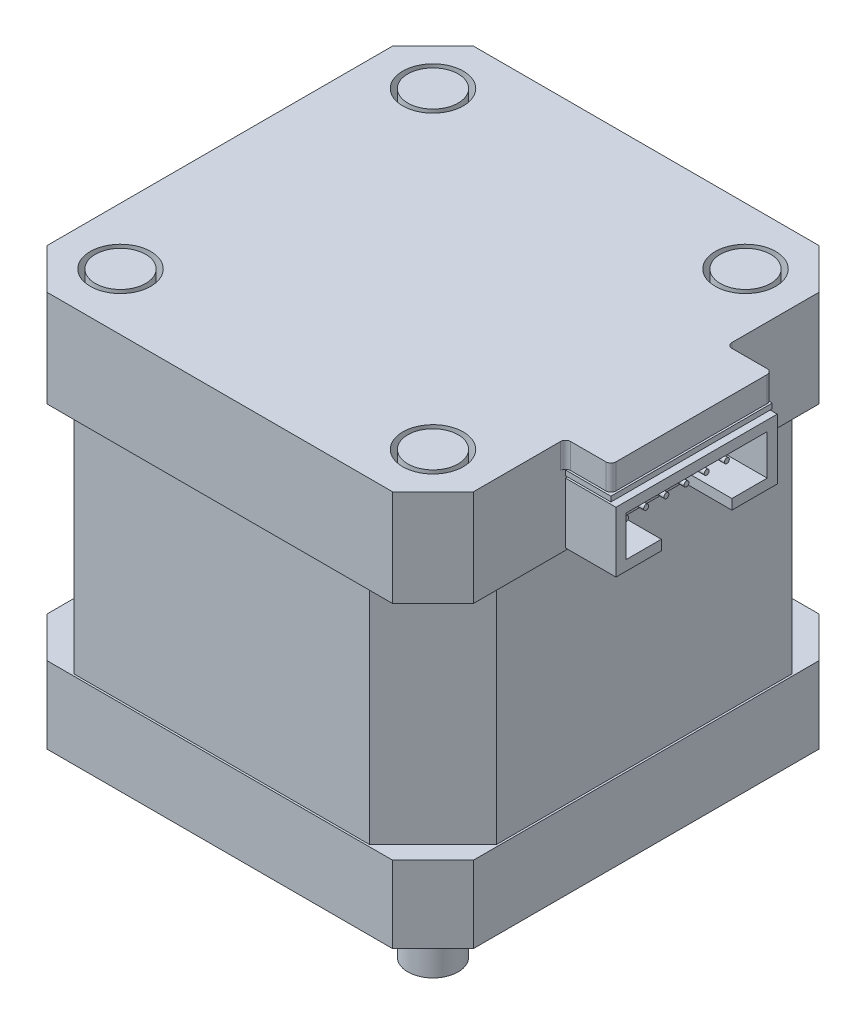
SolidWorks part; units mm, degrees
ref_plane "Front Plane" through (0, 0, 0) normal (0, 0, 1) x (1, 0, 0)
ref_plane "Top Plane" through (0, 0, 0) normal (0, 1, 0) x (1, 0, 0)
ref_plane "Right Plane" through (0, 0, 0) normal (1, 0, 0) x (0, 0, -1)
sketch "Sketch1" plane through (0, 0, 0) normal (0, 1, 0) x (1, 0, 0)
  line L1 (-21.15, -21.15) -> (21.15, -21.15)
  line L2 (-21.15, -21.15) -> (-21.15, 21.15)
  line L3 (-21.15, 21.15) -> (21.15, 21.15)
  line L4 (21.15, -21.15) -> (21.15, 21.15)
  line L5 (-21.15, -21.15) -> (21.15, 21.15) construction
  line L6 (-21.15, 21.15) -> (21.15, -21.15) construction
  point P0 (0, 0)
  dimension "D1" = 42.3
  dimension "D2" = 42.3
extrude "Boss-Extrude1" add sketch "Sketch1" along normal blind 39.25
chamfer "Chamfer1" distance 4 angle 45 8 edges at (-21.15, 19.625, -21.15) (21.15, 19.625, -21.15) (21.15, 19.625, 21.15) (-21.15, 19.625, 21.15) (21.15, 0, 0) (21.15, 39.25, 0) (-21.15, 39.25, 0) (-21.15, 0, 0)
sketch "Sketch2" plane through (19.15, 0, -19.15) normal (0.7071, 0, -0.7071) x (-0.7071, 0, -0.7071)
  line L0 (2.8284, 0) -> (-2.8284, 0) construction
  line L1 (-4.9984, 29.65) -> (5.0016, 29.65)
  line L2 (-4.9984, 29.65) -> (-4.9984, 7.6)
  line L3 (-4.9984, 7.6) -> (5.0016, 7.6)
  line L4 (5.0016, 29.65) -> (5.0016, 7.6)
  line L5 (-2.8284, 39.25) -> (2.8284, 39.25) construction
  line L6 (-2.8284, 0) -> (-2.8284, 39.25) construction
  line L8 (2.8284, 39.25) -> (2.8284, 0) construction
  dimension "D1" = 7.6
  dimension "D2" = 9.6
  dimension "D3" = 2.17
  dimension "D4" = 10
extrude "Cut-Extrude1" cut sketch "Sketch2" against normal blind 1.9
mirror "Mirror1" about plane through (0, 0, 0) normal (0, 0, 1) of "Cut-Extrude1"
mirror "Mirror2" about plane through (0, 0, 0) normal (1, 0, 0) of "Mirror1", "Cut-Extrude1"
sketch "Sketch3" plane through (0, 0, 0) normal (0, -1, 0) x (1, 0, 0)
  circle A0 centre (0, 0) radius 11
  dimension "D1" = 22
extrude "Boss-Extrude2" add sketch "Sketch3" along normal blind 1.9
sketch "Sketch4" plane through (0, 0, 0) normal (0, -1, 0) x (1, 0, 0)
  circle A0 centre (0, 0) radius 11.5
  circle A1 centre (0, 0) radius 11
  dimension "D1" = 0.5
extrude "Cut-Extrude2" cut sketch "Sketch4" against normal blind 2
sketch "Sketch5" plane through (0, -1.9, 0) normal (0, -1, 0) x (1, 0, 0)
  circle A0 centre (0, 0) radius 4.5
  dimension "D1" = 9
extrude "Cut-Extrude3" cut sketch "Sketch5" against normal blind 2
sketch "Sketch6" plane through (0, 0.1, 0) normal (0, -1, 0) x (1, 0, 0)
  circle A0 centre (0, 0) radius 2.5
  dimension "D1" = 5
extrude "Boss-Extrude3" add sketch "Sketch6" along normal blind 20
sketch "Sketch7" plane through (0, -19.9, 0) normal (0, -1, 0) x (1, 0, 0)
  line L0 (-2.5, 0) -> (0, -2.5)
  line L1 (0, 0) -> (0, -2.5) construction
  line L2 (0, 0) -> (-2.5, 0) construction
  arc A0 (-2.5, 0) -> (0, -2.5) centre (0, 0) ccw
  circle A1 centre (0, 0) radius 2.5 construction
  circle A2 centre (0, 0) radius 2.5 construction
extrude "Cut-Extrude4" cut sketch "Sketch7" against normal blind 15
sketch "Sketch8" plane through (0, 0, 0) normal (0, -1, 0) x (1, 0, 0)
  line L1 (-15.5, -15.5) -> (15.5, -15.5) construction
  line L2 (-15.5, -15.5) -> (-15.5, 15.5) construction
  line L3 (-15.5, 15.5) -> (15.5, 15.5) construction
  line L4 (15.5, -15.5) -> (15.5, 15.5) construction
  line L5 (-15.5, -15.5) -> (15.5, 15.5) construction
  line L6 (-15.5, 15.5) -> (15.5, -15.5) construction
  circle A0 centre (-15.5, 15.5) radius 1.5
  circle A1 centre (15.5, 15.5) radius 1.5
  circle A2 centre (15.5, -15.5) radius 1.5
  circle A3 centre (-15.5, -15.5) radius 1.5
  point P0 (0, 0)
  point P16 (0, 0)
  dimension "D4" = 3
  dimension "D1" = 31
  dimension "D2" = 31
  dimension "D3" = 4
extrude "Cut-Extrude5" cut sketch "Sketch8" against normal blind 4
sketch "Sketch10" plane through (-21.15, 0, 0) normal (-1, 0, 0) x (0, 0, 1)
  line L0 (-17.15, 7.6) -> (-14.463, 7.6) construction
  line L1 (-15.463, 7.6) -> (15.463, 7.6)
  line L2 (-15.463, 7.6) -> (-15.463, 29.65)
  line L3 (-15.463, 29.65) -> (15.463, 29.65)
  line L4 (15.463, 7.6) -> (15.463, 29.65)
  line L5 (21.15, 29.65) -> (14.463, 29.65) construction
  line L6 (-14.463, 7.6) -> (-14.463, 29.65) construction
  line L7 (14.463, 29.65) -> (14.463, 7.6) construction
  dimension "D1" = 1
  dimension "D2" = 1
extrude "Cut-Extrude6" cut sketch "Sketch10" against normal blind 0.2
pattern_circular "CirPattern1" count 4 every 90 about axis through (0, 0, 0) along (0, 1, 0) of "Cut-Extrude6"
sketch "Sketch11" plane through (21.15, 0, 0) normal (1, 0, 0) x (0, 0, -1)
  line L0 (-17.15, 39.25) -> (17.15, 39.25) construction
  line L1 (-8, 39.25) -> (8, 39.25)
  line L2 (-8, 39.25) -> (-8, 36.75)
  line L3 (-8, 36.75) -> (8, 36.75)
  line L4 (8, 39.25) -> (8, 36.75)
  line L6 (0, 0) -> (0, 39.25) construction
  point P9 (0, 39.25)
  dimension "D1" = 16
  dimension "D2" = 2.5
extrude "Boss-Extrude4" add sketch "Sketch11" along normal blind 4.5
fillet "Fillet1" radius 0.5 4 edges at (21.15, 38, -8) (25.65, 38, -8) (21.15, 38, 8) (25.65, 38, 8)
sketch "Sketch12" plane through (21.15, 0, 0) normal (1, 0, 0) x (0, 0, -1)
  line L0 (-7.5, 36.75) -> (7.5, 36.75) construction
  line L1 (-8, 36.55) -> (8, 36.55)
  line L2 (-8, 36.55) -> (-8, 36.05)
  line L3 (-8, 36.05) -> (8, 36.05)
  line L4 (8, 36.55) -> (8, 36.05)
  line L5 (-8, 39.25) -> (-8, 36.75) construction
  line L7 (8, 36.75) -> (8, 39.25) construction
  dimension "D1" = 0.2
  dimension "D2" = 0.5
extrude "Boss-Extrude5" add sketch "Sketch12" along normal blind 4.5
sketch "Sketch13" plane through (21.15, 0, 0) normal (1, 0, 0) x (0, 0, -1)
  line L0 (-3.5, 30.85) -> (-3.5, 29.85)
  line L1 (-8, 35.85) -> (8, 35.85)
  line L2 (-8, 35.85) -> (-8, 29.85)
  line L3 (-8, 29.85) -> (-3.5, 29.85)
  line L4 (8, 35.85) -> (8, 29.85)
  line L5 (-7, 34.85) -> (7, 34.85)
  line L6 (-7, 34.85) -> (-7, 30.85)
  line L7 (-7, 30.85) -> (-3.5, 30.85)
  line L8 (7, 34.85) -> (7, 30.85)
  line L9 (3.5, 30.85) -> (3.5, 29.85)
  line L10 (3.5, 30.85) -> (7, 30.85)
  line L11 (3.5, 29.85) -> (8, 29.85)
  line L12 (8, 36.05) -> (8, 36.55) construction
  line L13 (-8, 36.55) -> (-8, 36.05) construction
  line L14 (-8, 36.05) -> (8, 36.05) construction
  line L15 (14.663, 29.65) -> (-14.663, 29.65) construction
  dimension "D1" = 0.2
  dimension "D2" = 0.2
  dimension "D3" = 1
  dimension "D4" = 1
  dimension "D5" = 1
  dimension "D6" = 1
  dimension "D7" = 3.5
  dimension "D8" = 3.5
extrude "Boss-Extrude6" add sketch "Sketch13" along normal blind 5
sketch "Sketch14" plane through (21.15, 0, 0) normal (1, 0, 0) x (0, 0, -1)
  line L0 (-7, 32.35) -> (7, 32.35) construction
  line L1 (-7, 30.85) -> (-7, 34.85) construction
  line L2 (7, 34.85) -> (7, 30.85) construction
  line L3 (-3.5, 30.85) -> (-7, 30.85) construction
  circle A0 centre (-5, 32.35) radius 0.25
  circle A1 centre (-3, 32.35) radius 0.25
  circle A2 centre (-1, 32.35) radius 0.25
  circle A3 centre (1, 32.35) radius 0.25
  circle A4 centre (3, 32.35) radius 0.25
  circle A5 centre (5, 32.35) radius 0.25
  dimension "D2" = 0.5
  dimension "D1" = 1.5
  dimension "D3" = 2
  dimension "D4" = 6
extrude "Boss-Extrude7" add sketch "Sketch14" along normal blind 3
sketch "Sketch15" plane through (0, 39.25, 0) normal (0, 1, 0) x (1, 0, 0)
  line L1 (-15.5, -15.5) -> (15.5, -15.5) construction
  line L2 (-15.5, -15.5) -> (-15.5, 15.5) construction
  line L3 (-15.5, 15.5) -> (15.5, 15.5) construction
  line L4 (15.5, -15.5) -> (15.5, 15.5) construction
  line L5 (-15.5, -15.5) -> (15.5, 15.5) construction
  line L6 (-15.5, 15.5) -> (15.5, -15.5) construction
  circle A0 centre (-15.5, 15.5) radius 3
  circle A1 centre (15.5, 15.5) radius 3
  circle A2 centre (15.5, -15.5) radius 3
  circle A3 centre (-15.5, -15.5) radius 3
  circle A4 centre (-15.5, 15.5) radius 2.5
  circle A5 centre (15.5, 15.5) radius 2.5
  circle A6 centre (15.5, -15.5) radius 2.5
  circle A7 centre (-15.5, -15.5) radius 2.5
  point P0 (0, 0)
  point P16 (0, 0)
  dimension "D3" = 6
  dimension "D5" = 5
  dimension "D1" = 31
  dimension "D2" = 31
  dimension "D4" = 4
extrude "Cut-Extrude7" cut sketch "Sketch15" against normal blind 3
